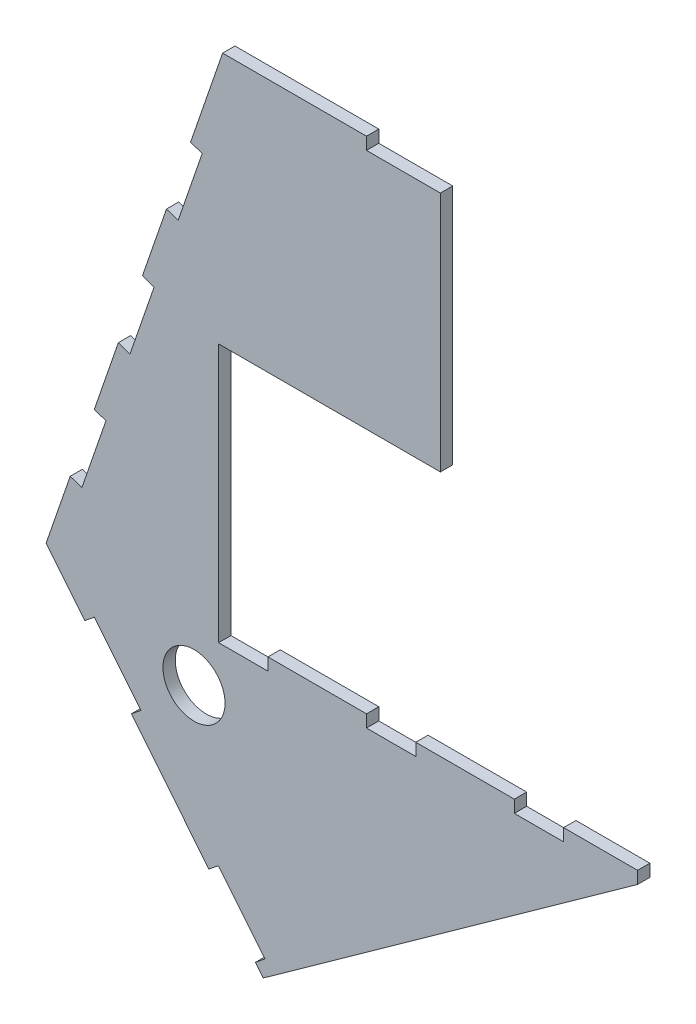
SolidWorks part; units mm, degrees
ref_plane "Front Plane" through (0, 0, 0) normal (0, 0, 1) x (1, 0, 0)
ref_plane "Top Plane" through (0, 0, 0) normal (0, 1, 0) x (1, 0, 0)
ref_plane "Right Plane" through (0, 0, 0) normal (1, 0, 0) x (0, 0, -1)
sketch "Sketch1" plane through (0, 0, 0) normal (0, 0, 1) x (1, 0, 0)
  line L0 (0, 0) -> (152.4, 0) construction
  line L7 (45.4819, 132.0889) -> (37.2124, 108.0728)
  line L8 (0, 0) -> (9.9704, -12.3124)
  line L9 (55.9466, -69.0883) -> (152.4, 0)
  line L10 (95.25, 0) -> (95.25, 3.175)
  line L11 (133.35, 0) -> (120.65, 0)
  line L12 (133.35, 0) -> (133.35, 3.175)
  line L14 (120.65, 0) -> (120.65, 3.175)
  line L15 (95.25, 0) -> (82.55, 0)
  line L16 (82.55, 0) -> (82.55, 3.175)
  line L18 (57.15, 0) -> (57.15, 3.175)
  line L19 (57.15, 0) -> (44.45, 0)
  line L20 (44.45, 0) -> (44.45, 3.175)
  line L25 (101.6, 128.9139) -> (82.55, 128.9139)
  line L26 (82.55, 128.9139) -> (82.55, 132.0889)
  line L27 (82.55, 132.0889) -> (45.4819, 132.0889)
  line L28 (37.2124, 108.0728) -> (40.2145, 107.0391)
  line L29 (40.2145, 107.0391) -> (34.0124, 89.027)
  line L30 (34.0124, 89.027) -> (31.0104, 90.0606)
  line L31 (31.0104, 90.0606) -> (24.8083, 72.0485)
  line L32 (24.8083, 72.0485) -> (27.8103, 71.0148)
  line L33 (27.8103, 71.0148) -> (21.6082, 53.0027)
  line L34 (21.6082, 53.0027) -> (18.6062, 54.0364)
  line L35 (12.4041, 36.0243) -> (15.4062, 34.9906)
  line L36 (15.4062, 34.9906) -> (9.2041, 16.9784)
  line L37 (9.2041, 16.9784) -> (6.2021, 18.0121)
  line L38 (6.2021, 18.0121) -> (0, 0)
  line L39 (18.6062, 54.0364) -> (12.4041, 36.0243)
  line L40 (53.9284, -66.596) -> (56.3958, -64.5979)
  line L41 (56.3958, -64.5979) -> (44.4073, -49.7933)
  line L42 (44.4073, -49.7933) -> (41.9398, -51.7914)
  line L43 (21.9589, -27.117) -> (24.4263, -25.1189)
  line L44 (24.4263, -25.1189) -> (12.4378, -10.3143)
  line L45 (12.4378, -10.3143) -> (9.9704, -12.3124)
  line L46 (21.9589, -27.117) -> (41.9398, -51.7914)
  line L47 (53.9284, -66.596) -> (55.9466, -69.0883)
  line L48 (44.45, 3.175) -> (44.45, 66.675)
  line L49 (44.45, 66.675) -> (101.6, 66.675)
  line L50 (57.15, 3.175) -> (82.55, 3.175)
  line L51 (95.25, 3.175) -> (120.65, 3.175)
  line L52 (133.35, 3.175) -> (152.4, 3.175)
  line L53 (152.4, 0) -> (152.4, 3.175)
  line L54 (101.6, 128.9139) -> (101.6, 66.675)
  line L55 (0, 0) -> (0, -48.4793) construction
  circle A0 centre (38.1, -12.7) radius 8
  dimension "D8" = 16
  dimension "D9" = 38.1
  dimension "D1" = 71
  dimension "D2" = 152.4
  dimension "D3" = 139.7
  dimension "D4" = 88.9
  dimension "D5" = 51
  dimension "D6" = 12.7
  dimension "D7" = 3.175
  dimension "D10" = 12.7
  dimension "D11" = 19.05
  dimension "D14" = 3.175
  dimension "D15" = 19.05
  dimension "D16" = 25.4
  dimension "D17" = 19.05
  dimension "D18" = 3.175
  dimension "D19" = 3.175
  dimension "D20" = 19.05
  dimension "D21" = 19.05
  dimension "D22" = 19.05
  dimension "D23" = 19.05
  dimension "D24" = 19.05
  dimension "D25" = 31.75
  dimension "D26" = 3.175
  dimension "D27" = 3.175
  dimension "D28" = 63.5
extrude "Boss-Extrude1" add sketch "Sketch1" along normal blind 3.175
